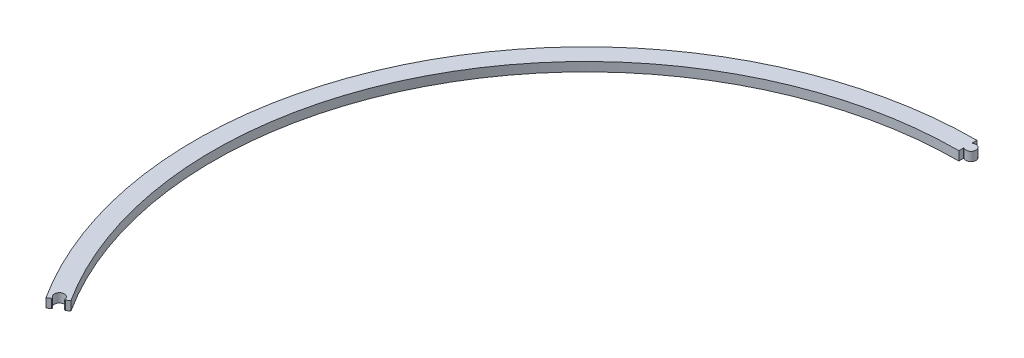
SolidWorks part; units mm, degrees
ref_plane "Front Plane" through (0, 0, 0) normal (0, 0, 1) x (1, 0, 0)
ref_plane "Top Plane" through (0, 0, 0) normal (0, 1, 0) x (1, 0, 0)
ref_plane "Right Plane" through (0, 0, 0) normal (1, 0, 0) x (0, 0, -1)
sketch "Sketch1" plane through (0, 0, 0) normal (0, 1, 0) x (1, 0, 0)
  line L0 (0, 0) -> (0, 105.0393) construction
  line L1 (0, 0) -> (-88.4532, -56.6506) construction
  line L2 (0, 103.6) -> (0, 105.0393)
  line L3 (-91.4516, -58.571) -> (-90.2395, -57.7947) construction
  line L4 (0, 106.1) -> (0.875, 106.1) construction
  line L5 (0, 107.1607) -> (0, 108.6) construction
  line L6 (0, 107.1607) -> (0, 108.6)
  line L7 (0, 103.6) -> (0, 108.6) construction
  line L8 (-89.8183, -56.4859) -> (-89.3464, -57.2227) construction
  line L9 (-90.2395, -57.7947) -> (-91.4516, -58.571) construction
  line L10 (-88.4532, -56.6506) -> (-87.2411, -55.8744) construction
  line L11 (-91.4516, -58.571) -> (-87.2411, -55.8744) construction
  line L12 (-88.4532, -56.6506) -> (-87.2411, -55.8744)
  line L13 (-91.4516, -58.571) -> (-90.2395, -57.7947)
  arc A0 (0, 108.6) -> (-91.4516, -58.571) centre (0, 0) ccw
  arc A1 (0, 103.6) -> (-87.2411, -55.8744) centre (0, 0) ccw
  arc A2 (0, 105.0393) -> (0, 107.1607) centre (0.875, 106.1) ccw
  arc A3 (-88.4532, -56.6506) -> (-90.2395, -57.7947) centre (-89.8183, -56.4859) ccw
  arc A5 (-89.3464, -57.2227) -> (0, 106.1) centre (0, 0) cw construction
  point P12 (0, 106.1)
  dimension "D1" = 106.1
  dimension "D2" = 2.5
  dimension "D4" = 5
  dimension "D5" = 2.75
  dimension "D7" = 108.6
  dimension "D3" = 122.638
  dimension "D6" = 0.875
extrude "Boss-Extrude1" add sketch "Sketch1" along normal blind 2.5
fillet "Fillet1" radius 0.2 2 edges at (-88.4532, 1.25, 56.6506) (-90.2395, 1.25, 57.7947)
fillet "Fillet2" radius 0.1 2 edges at (0, 1.25, -107.1607) (0, 1.25, -105.0393)
